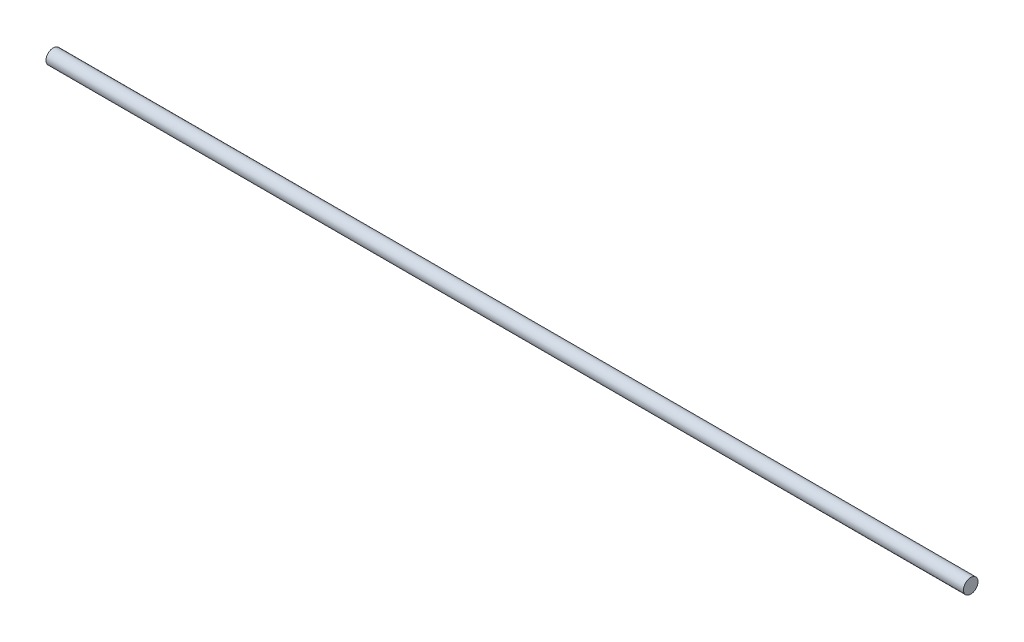
SolidWorks part; units mm, degrees
material "AISI 1020"
ref_plane "Front Plane" through (0, 0, 0) normal (0, 0, 1) x (1, 0, 0)
ref_plane "Top Plane" through (0, 0, 0) normal (0, 1, 0) x (1, 0, 0)
ref_plane "Right Plane" through (0, 0, 0) normal (1, 0, 0) x (0, 0, -1)
sketch "Sketch1" plane through (0, 0, 0) normal (1, 0, 0) x (0, 0, -1)
  circle A0 centre (0, 0) radius 3.175
  dimension "D1" = 6.35
extrude "Boss-Extrude1" add sketch "Sketch1" along normal blind 400.05
equation "\"OD\"= 1 / 4"
equation "\"L\" = 15.75"
equation "\"D1@Boss-Extrude1\"=\"L\""
equation "\"D1@Sketch1\"=\"OD\""
